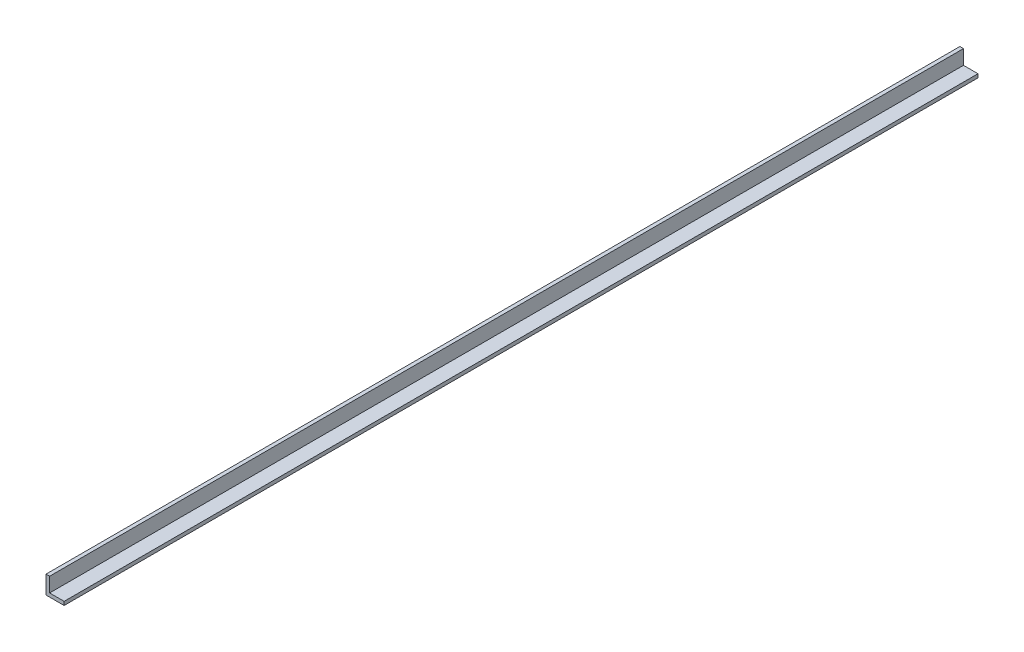
SolidWorks part; units mm, degrees
ref_plane "Front" through (0, 0, 0) normal (0, 0, 1) x (1, 0, 0)
ref_plane "Top" through (0, 0, 0) normal (0, 1, 0) x (1, 0, 0)
ref_plane "Right" through (0, 0, 0) normal (1, 0, 0) x (0, 0, -1)
sketch "Эскиз1" plane through (0, 0, 0) normal (0, 0, 1) x (1, 0, 0)
  line L0 (-10, 20) -> (-10, 0)
  line L1 (-10, 0) -> (10, 0)
  line L2 (10, 0) -> (10, 4)
  line L3 (10, 4) -> (-6, 4)
  line L4 (-6, 4) -> (-6, 20)
  line L5 (-6, 20) -> (-10, 20)
  dimension "D1" = 20
  dimension "D2" = 4
extrude "Бобышка-Вытянуть1" add sketch "Эскиз1" along normal blind 1008
